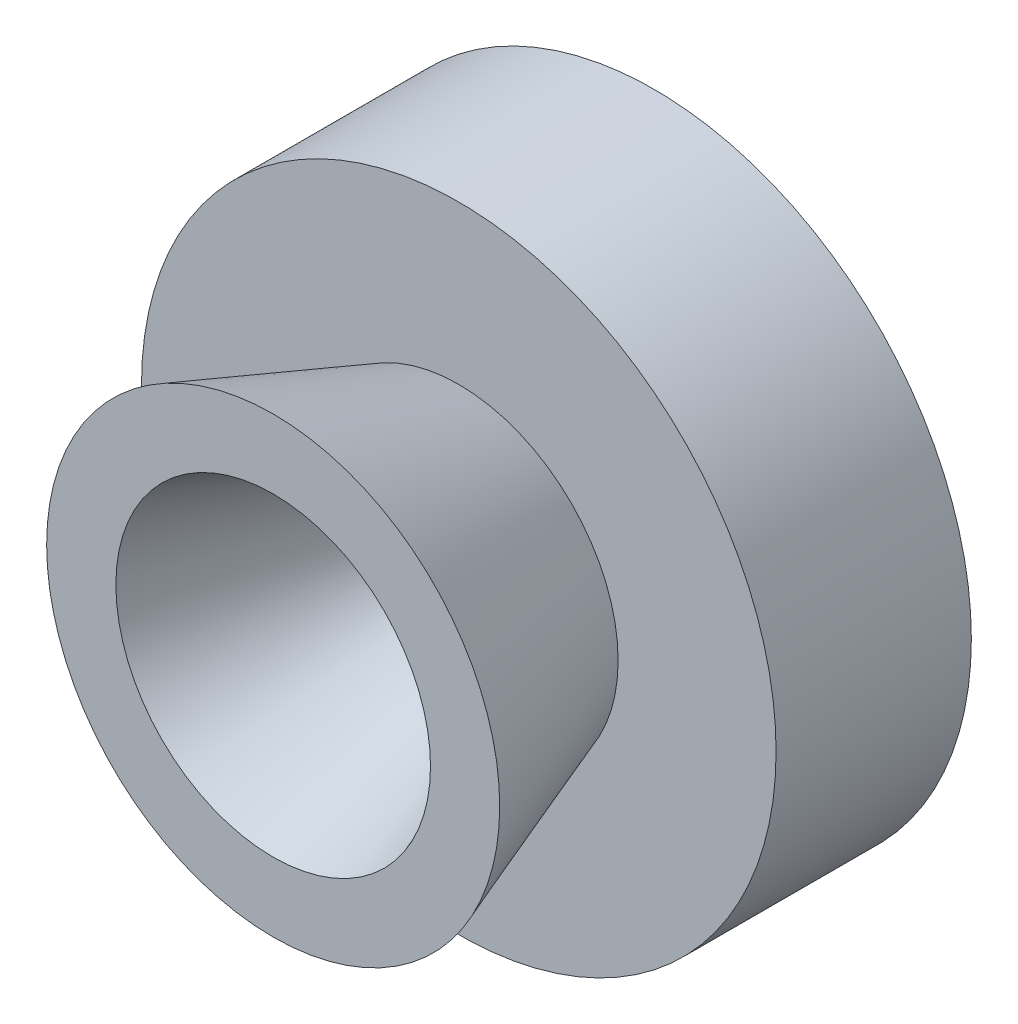
SolidWorks part; units mm, degrees
ref_plane "Plano frontal" through (0, 0, 0) normal (0, 0, 1) x (1, 0, 0)
ref_plane "Plano superior" through (0, 0, 0) normal (0, 1, 0) x (1, 0, 0)
ref_plane "Plano direito" through (0, 0, 0) normal (1, 0, 0) x (0, 0, -1)
sketch "Esboço1" plane through (0, 0, 0) normal (0, 0, 1) x (1, 0, 0)
  circle A0 centre (0, 0) radius 9.75
  dimension "D1" = 19.5
extrude "Ressalto-extrusão1" add sketch "Esboço1" against normal blind 6
sketch "Esboço2" plane through (0, 0, 0) normal (0, 1, 0) x (1, 0, 0)
  line L0 (0, 0) -> (-4.8962, 0)
  line L1 (-4.8962, 0) -> (-6.9607, -5.7027)
  line L2 (-6.9607, -5.7027) -> (0, -5.7027)
  line L3 (0, -5.7027) -> (0, 0)
revolve "Revolução1" add sketch "Esboço2" angle 360 about L3
shell "Casca9" thickness 2
sketch "Esboço3" plane through (0, 0, -4) normal (0, 0, 1) x (1, 0, 0)
  circle A0 centre (0, 0) radius 2.0451 construction
  circle A1 centre (0, 0) radius 7.75
  circle A2 centre (0, 0) radius 7.75
  circle A3 centre (0, 0) radius 2.0451
  dimension "D1" = 0
extrude "Corte-extrusão2" cut sketch "Esboço3" against normal through all contours A3
sketch "Esboço4" plane through (0, 0, -6) normal (0, 0, -1) x (-1, 0, 0)
  circle A0 centre (0, 0) radius 5.75
  circle A1 centre (0, 0) radius 9.75 construction
  dimension "D1" = 4
extrude "Corte-extrusão3" cut sketch "Esboço4" against normal blind 5
